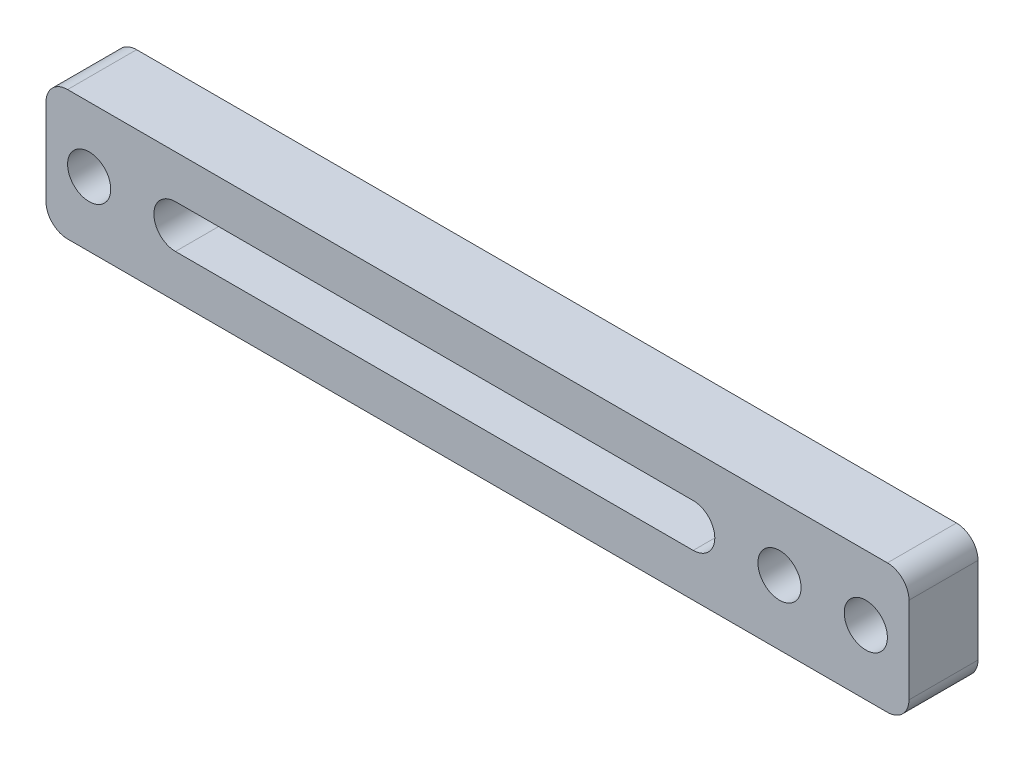
SolidWorks part; units mm, degrees
ref_plane "Спереди" through (0, 0, 0) normal (0, 0, 1) x (1, 0, 0)
ref_plane "Сверху" through (0, 0, 0) normal (0, 1, 0) x (1, 0, 0)
ref_plane "Справа" through (0, 0, 0) normal (1, 0, 0) x (0, 0, -1)
sketch "Эскиз1" plane through (0, 0, 0) normal (0, 0, 1) x (1, 0, 0)
  line L1 (0, 0) -> (100, 0)
  line L2 (0, 0) -> (0, 15)
  line L3 (0, 15) -> (100, 15)
  line L4 (100, 0) -> (100, 15)
  dimension "D1" = 100
  dimension "D2" = 15
extrude "Вытянуть1" add sketch "Эскиз1" along normal blind 8
sketch "Эскиз2" plane through (0, 0, 8) normal (0, 0, 1) x (1, 0, 0)
  line L0 (0, 15) -> (0, 0) construction
  line L1 (15, 10) -> (75, 10)
  line L3 (15, 5) -> (75, 5)
  line L4 (100, 0) -> (100, 15) construction
  line L5 (-14.6814, 7.5) -> (66.4971, 7.5) construction
  circle A0 centre (5, 7.5) radius 2.5
  arc A1 (75, 10) -> (75, 5) centre (75, 7.5) cw
  arc A2 (15, 10) -> (15, 5) centre (15, 7.5) ccw
  circle A3 centre (95, 7.5) radius 2.5
  circle A4 centre (85, 7.5) radius 2.5
  point P9 (0, 7.5)
  dimension "D4" = 5
  dimension "D1" = 5
  dimension "D2" = 5
  dimension "D3" = 10
  dimension "D5" = 10
  dimension "D6" = 5
  dimension "D7" = 10
extrude "Вытянуть2" cut sketch "Эскиз2" against normal blind 8
fillet "Скругление2" radius 2.5 4 edges at (0, 0, 4) (0, 15, 4) (100, 0, 4) (100, 15, 4)
